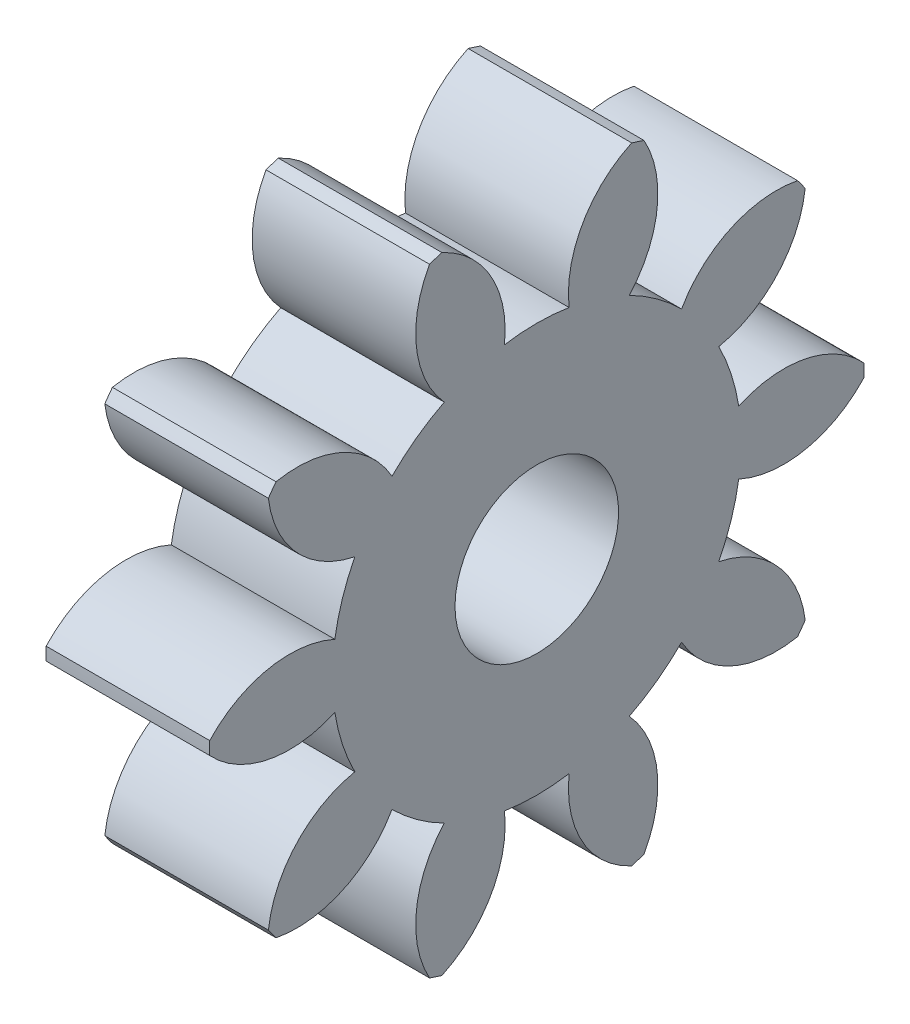
SolidWorks part; units mm, degrees
ref_plane "Plane1" through (0, 0, 0) normal (0, 0, 1) x (1, 0, 0)
ref_plane "Plane2" through (0, 0, 0) normal (0, 1, 0) x (1, 0, 0)
ref_plane "Plane3" through (0, 0, 0) normal (1, 0, 0) x (0, 0, -1)
sketch "HoldingSke" plane through (0, 0, 0) normal (0, 1, 0) x (1, 0, 0)
  line L0 (0, 0) -> (0.9848, -0.1736)
  line L1 (-15, 0) -> (100, 0) construction
  line L2 (0, 0) -> (-2.1039, 2.3779)
  line L3 (0, 0) -> (-11.863, 4.5341)
  line L4 (0, 0) -> (8.5048, 1.4996)
  line L5 (0, 0) -> (-46.8476, -17.4728)
  line L6 (0, 0) -> (-2.4869, -1.6779)
  line L7 (-2.1039, 2.3779) -> (8.6586, 51.2059)
  line L8 (-76.2, 54.61) -> (-75.7, 54.61)
  line L9 (-71.009, 38.7566) -> (-53.1078, 45.2721)
  line L10 (-76.2, 71.12) -> (104.1128, 71.12)
  line L11 (0, 0) -> (-3, 0)
  line L12 (-76.2, 101.6) -> (-76.162, 101.6)
  line L13 (24.9733, 27.94) -> (52.9518, 28.4284)
  line L14 (24.9733, 27.94) -> (24.9743, 27.94)
  line L15 (24.9733, 27.94) -> (100.4006, 29.5858)
  line L16 (-63.627, -1) -> (-12.827, -1)
  circle A0 centre (0, 0) radius 1.5
  circle A1 centre (0, 0) radius 3.749
  circle A2 centre (0, 0) radius 37.5
  circle A3 centre (0, 0) radius 1.5
  dimension "MHD" = 7.498
  dimension "Hub_dia" = 75
  dimension "Bore" = 3
  dimension "MBD" = 3
  dimension "Num_teeth" = 10
  dimension "Pitch" = 1
  dimension "Overall_len" = 50
  dimension "Show_teeth" = 10
  dimension "Thickness" = 3
  dimension "OAL" = 50.0001
  dimension "T_dim" = 0.5
  dimension "Ap" = 20
  dimension "H" = 19.05
  dimension "Pitch_radius" = 180.3128
  dimension "Width" = 3
  dimension "Backlash" = 0.038
  dimension "Addendum_fac" = 1
  dimension "Dedendum_fac" = 1.25
  dimension "Clearance_fac" = 0.25
  dimension "Dedendum_add" = 0.001
  dimension "Module" = 1
sketch "BasProSke" plane through (0, 0, 0) normal (0, 1, 0) x (1, 0, 0)
  line L0 (-10, 0) -> (60, 0) construction
  line L1 (0, 0) -> (0, 6)
  line L2 (0, 0) -> (3, 0)
  line L3 (3, 0) -> (3, 6)
  line L4 (3, 6) -> (0, 6)
  dimension "Thickness" = 3
  dimension "Diameter" = 12
revolve "Base-Revolve" add sketch "BasProSke" angle 360 about L0
sketch "TooCutSke" plane through (0, 0, 0) normal (1, 0, 0) x (0, 0, -1)
  line L1 (0, 0) -> (0, 107) construction
  line L2 (0, 0) -> (-0.8485, 4.9275) construction
  line L3 (0, 0) -> (-3.0584, 9.4126) construction
  line L4 (-0.8485, 4.9275) -> (-1.5292, 4.7063) construction
  arc A0 (0.5928, 3.7018) -> (-0.5928, 3.7018) centre (0, 0) ccw
  arc A1 (1.7758, 5.7578) -> (-1.7758, 5.7578) centre (0, 0) ccw
  circle A2 centre (0, 0) radius 5 construction
  circle A3 centre (0, 0) radius 4.6985 construction
  arc A4 (-0.5928, 3.7018) -> (-1.7758, 5.7578) centre (-2.5801, 3.9267) ccw
  arc A5 (1.7758, 5.7578) -> (0.5928, 3.7018) centre (2.5801, 3.9267) ccw
  dimension "Root_dia" = 7.498
  dimension "Overcut_dia" = 12.0508
  dimension "Pitch_dia" = 10
  dimension "Base_dia" = 9.3969
  dimension "Flank_rad" = 2
  dimension "Half_ang" = 18
  dimension "Half_CT" = 0.7157
extrude "ToothCut" cut sketch "TooCutSke" along normal through all
fillet "Breaks" [suppressed] radius 0.02
fillet "RootFillets" [suppressed] radius 0.251
pattern_circular "TeethCuts" count 10 every 36 about axis through (-10, 0, 0) along (1, 0, 0) of "ToothCut", "RootFillets", "Breaks"
sketch "HubNeaOneSke" plane through (0, 0, 0) normal (-1, 0, 0) x (0, 0, 1)
  circle A0 centre (0, 0) radius 3.749
  dimension "Diameter" = 7.498
extrude "HubNearOne" [suppressed] add sketch "HubNeaOneSke" along normal blind 47.0001
sketch "HubNeaBotSke" plane through (0, 0, 0) normal (-1, 0, 0) x (0, 0, 1)
  circle A0 centre (0, 0) radius 3.749
  dimension "Diameter" = 7.498
extrude "HubNearBoth" [suppressed] add sketch "HubNeaBotSke" along normal blind 23.5
ref_plane "FarPln" through (3, 0, 0) normal (1, 0, 0) x (0, 0, -1)
sketch "HubFarSke" plane through (3, 0, 0) normal (1, 0, 0) x (0, 0, -1)
  circle A0 centre (0, 0) radius 3.749
  dimension "Diameter" = 7.498
extrude "HubFar" [suppressed] add sketch "HubFarSke" along normal blind 23.5
sketch "BorSke" plane through (0, 0, 0) normal (1, 0, 0) x (0, 0, -1)
  circle A0 centre (0, 0) radius 1.5
  dimension "Diameter" = 3
extrude "Bore" cut sketch "BorSke" along normal mid plane 100.0001
sketch "KeySke" plane through (0, 0, 0) normal (1, 0, 0) x (0, 0, -1)
  line L0 (-0.6, 0) -> (-0.6, 2)
  line L1 (-0.6, 2) -> (0.6, 2)
  line L2 (0.6, 2) -> (0.6, 0)
  line L3 (0, 0) -> (0, 34) construction
  line L4 (-0.6, 0) -> (0.6, 0)
  dimension "Offset" = 2
  dimension "Width" = 1.2
extrude "Keyway" [suppressed] cut sketch "KeySke" along normal mid plane 100.0001
pattern_circular "Keyway2" [suppressed] count 2 every 90 about axis through (-10, 0, 0) along (1, 0, 0)
equation "' \"Module@HoldingSke\" = 6.35"
equation "' \"Num_teeth@HoldingSke\" = 12"
equation "' \"Ap@HoldingSke\" =  20"
equation "' \"Ap@HoldingSke\" = 20"
equation "' \"Width@HoldingSke\" = 0.5 * 25.4"
equation "' \"Hub_dia@HoldingSke\"= 1 * 25.4"
equation "' \"Hub_dia@HoldingSke\" = 1 * 25.4"
equation "' \"Overall_len@HoldingSke\" = 1.0 * 25.4"
equation "' \"Bore@HoldingSke\" = 0.75 * 25.4"
equation "' \"T_dim@HoldingSke\" = 0.1 * 25.4"
equation "' \"Width@KeySke\" = 0.25 * 25.4"
equation "' \"Show_teeth@HoldingSke\" = 13"
equation "' \"Backlash@HoldingSke\" = 0.009 * 25.4"
equation "' \"Addendum_fac@HoldingSke\" = 1.0"
equation "' \"Dedendum_fac@HoldingSke\" = 1.25"
equation "' \"Dedendum_add@HoldingSke\" = 0.00005 * 25.4"
equation "' \"Clearance_fac@HoldingSke\" = 0.25"
equation "\"Pitch@HoldingSke\" = 1 / \"Module@HoldingSke\""
equation "\"Overcut_dia@TooCutSke\" = (\"Num_teeth@HoldingSke\" + 2 * \"Addendum_fac@HoldingSke\") / \"Pitch@HoldingSke\" + 0.002 * 25.4"
equation "\"Pitch_dia@TooCutSke\" = \"Num_teeth@HoldingSke\" / \"Pitch@HoldingSke\""
equation "\"Base_dia@TooCutSke\" = \"Num_teeth@HoldingSke\" / \"Pitch@HoldingSke\" * cos((\"Ap@HoldingSke\"  * 3.14159265 / 180))"
equation "\"Root_dia@TooCutSke\" = (\"Num_teeth@HoldingSke\" + 2) / \"Pitch@HoldingSke\" - 2 * (\"Addendum_fac@HoldingSke\" + \"Dedendum_fac@HoldingSke\") / \"Pitch@HoldingSke\" - \"Dedendum_add@HoldingSke\" * 2"
equation "\"Half_ang@TooCutSke\" = 180 / \"Num_teeth@HoldingSke\""
equation "\"Half_CT@TooCutSke\" = \"Num_teeth@HoldingSke\" / \"Pitch@HoldingSke\" * sin((3.14159265 / 2 / \"Num_teeth@HoldingSke\")) / 2 - 7 * \"Backlash@HoldingSke\" / 4"
equation "\"Flank_rad@TooCutSke\" = \"Num_teeth@HoldingSke\" / \"Pitch@HoldingSke\" / 5"
equation "\"Radius@RootFillets\" = \"Clearance_fac@HoldingSke\" / \"Pitch@HoldingSke\" + \"Dedendum_add@HoldingSke\""
equation "\"Break_rad@Breaks\" = 0.02 / \"Pitch@HoldingSke\""
equation "\"Thickness@HoldingSke\" = \"Width@HoldingSke\""
equation "\"OAL@HoldingSke\" = \"Thickness@HoldingSke\""
equation "\"MHD@HoldingSke\" = (\"Num_teeth@HoldingSke\" + 2) / \"Pitch@HoldingSke\" - 2 * (\"Addendum_fac@HoldingSke\" + \"Dedendum_fac@HoldingSke\")  / \"Pitch@HoldingSke\" - \"Dedendum_add@HoldingSke\" * 2"
equation "\"MBD@HoldingSke\" = (\"Num_teeth@HoldingSke\" + 2) / \"Pitch@HoldingSke\" - 2 * (\"Addendum_fac@HoldingSke\" + \"Dedendum_fac@HoldingSke\")  / \"Pitch@HoldingSke\" - \"Dedendum_add@HoldingSke\" * 2 - 0.002 * 25.4"
equation "\"MHD@HoldingSke\" = ((sgn( \"MHD@HoldingSke\" - \"Hub_dia@HoldingSke\" )-1)*( \"MHD@HoldingSke\" - \"Hub_dia@HoldingSke\" ))/-2+ \"Hub_dia@HoldingSke\""
equation "\"MBD@HoldingSke\" = ((sgn( \"MBD@HoldingSke\" - \"Bore@HoldingSke\" )-1)*( \"MBD@HoldingSke\" - \"Bore@HoldingSke\" ))/-2+ \"Bore@HoldingSke\""
equation "\"OAL@HoldingSke\" = ((sgn( \"OAL@HoldingSke\" - \"Overall_len@HoldingSke\" )+1)*( \"OAL@HoldingSke\" - \"Overall_len@HoldingSke\" ))/2 + \"Overall_len@HoldingSke\" + 0.000002 * 25.4"
equation "\"Num_teeth@TeethCuts\" = int( \"Show_teeth@HoldingSke\" ) + 1"
equation "\"Num_teeth@TeethCuts\" = ((sgn( \"Num_teeth@TeethCuts\" - \"Num_teeth@HoldingSke\" )-1)*( \"Num_teeth@TeethCuts\" - \"Num_teeth@HoldingSke\" ))/-2+ \"Num_teeth@HoldingSke\""
equation "\"Num_teeth@TeethCuts\" = ((sgn( \"Num_teeth@TeethCuts\" - 2.0)+1)*( \"Num_teeth@TeethCuts\" - 2.0))/2 +2.0"
equation "\"Angle@TeethCuts\" = 360.0 / \"Num_teeth@HoldingSke\""
equation "\"Diameter@BasProSke\" = (\"Num_teeth@HoldingSke\" + 2 * \"Addendum_fac@HoldingSke\") / \"Pitch@HoldingSke\""
equation "\"Thickness@BasProSke\"  = \"Thickness@HoldingSke\""
equation "' \"Fillet_rad@BasProSke\" =  \"Thickness@HoldingSke\" * 0.05"
equation "' \"Fillet_rad@BasProSke\" = \"Thickness@HoldingSke\" * 0.05"
equation "\"MHD@HoldingSke\" = ((sgn( \"MHD@HoldingSke\" - \"Root_dia@TooCutSke\" )-1)*( \"MHD@HoldingSke\" - \"Root_dia@TooCutSke\" ))/-2+ \"Root_dia@TooCutSke\""
equation "\"Diameter@HubNeaOneSke\" = \"MHD@HoldingSke\""
equation "\"Length@HubNearOne\" = \"OAL@HoldingSke\" - \"Thickness@BasProSke\""
equation "\"Diameter@HubNeaBotSke\" = \"MHD@HoldingSke\""
equation "\"Length@HubNearBoth\" = ( \"OAL@HoldingSke\" - \"Thickness@BasProSke\" ) / 2.0"
equation "\"Thickness@FarPln\" = \"Thickness@BasProSke\""
equation "\"Diameter@HubFarSke\" = \"MHD@HoldingSke\""
equation "\"Length@HubFar\" = ( \"OAL@HoldingSke\" - \"Thickness@BasProSke\" ) / 2.0"
equation "\"Diameter@BorSke\" = \"MBD@HoldingSke\""
equation "\"D1@Bore\" = \"OAL@HoldingSke\" * 2.0"
equation "\"D1@Keyway\" = \"OAL@HoldingSke\" * 2.0"
equation "\"Offset@KeySke\" = \"T_dim@HoldingSke\" + \"MBD@HoldingSke\" / 2.0"
